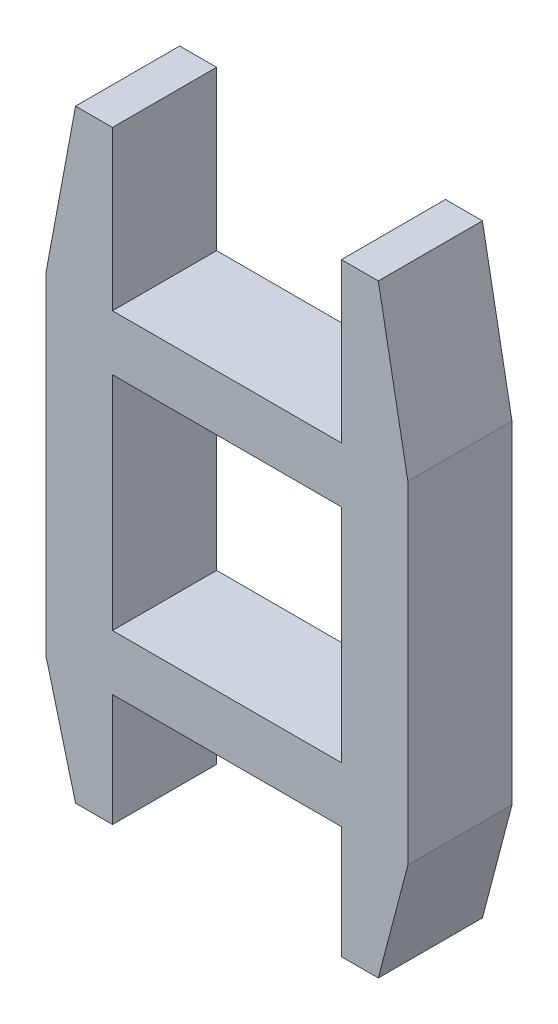
SolidWorks part; units mm, degrees
material "Acrylic (Medium-high impact)"
ref_plane "Front Plane" through (0, 0, 0) normal (0, 0, 1) x (1, 0, 0)
ref_plane "Top Plane" through (0, 0, 0) normal (0, 1, 0) x (1, 0, 0)
ref_plane "Right Plane" through (0, 0, 0) normal (1, 0, 0) x (0, 0, -1)
sketch "Sketch1" plane through (0, 0, 0) normal (0, 0, 1) x (1, 0, 0)
  line L0 (1247.2096, 961.8772) -> (1247.2096, 949.8772)
  line L1 (1263.2096, 948.3772) -> (1243.6096, 948.3772) construction
  line L2 (1247.2096, 946.8772) -> (1243.6096, 946.8772) construction
  line L3 (1247.2096, 961.8772) -> (1259.6096, 961.8772)
  line L4 (1245.2096, 973.4772) -> (1247.2096, 973.4772)
  line L5 (1247.2096, 973.4772) -> (1247.2096, 964.8772)
  line L6 (1247.2096, 955.8772) -> (1259.6096, 955.8772) construction
  line L7 (1259.6096, 964.8772) -> (1247.2096, 964.8772)
  line L8 (1243.6096, 964.8772) -> (1243.6096, 946.8772)
  line L9 (1243.6096, 946.8772) -> (1245.2096, 940.7772)
  line L10 (1247.2096, 964.8772) -> (1243.6096, 964.8772) construction
  line L11 (1259.6096, 946.8772) -> (1247.2096, 946.8772)
  line L12 (1243.6096, 964.8772) -> (1245.2096, 973.4772)
  line L13 (1247.2096, 940.7772) -> (1247.2096, 946.8772)
  line L14 (1245.2096, 940.7772) -> (1247.2096, 940.7772)
  line L15 (1247.2096, 949.8772) -> (1259.6096, 949.8772)
  line L16 (1259.6096, 964.8772) -> (1263.2096, 964.8772) construction
  line L17 (1259.6096, 946.8772) -> (1263.2096, 946.8772) construction
  line L18 (1261.6096, 940.7772) -> (1259.6096, 940.7772)
  line L19 (1253.4096, -37.9351) -> (1253.4096, 49962.0649) construction
  line L20 (1259.6096, 940.7772) -> (1259.6096, 946.8772)
  line L21 (1263.2096, 964.8772) -> (1261.6096, 973.4772)
  line L22 (1263.2096, 946.8772) -> (1261.6096, 940.7772)
  line L23 (1263.2096, 964.8772) -> (1263.2096, 946.8772)
  line L24 (1259.6096, 973.4772) -> (1259.6096, 964.8772)
  line L25 (1261.6096, 973.4772) -> (1259.6096, 973.4772)
  line L26 (1263.2096, 963.3772) -> (1243.6096, 963.3772) construction
  line L27 (1259.6096, 961.8772) -> (1259.6096, 949.8772)
  point P2 (1263.2096, 955.8772)
  point P14 (1243.6096, 955.8772)
  point P15 (1253.4096, 964.8772)
  point P20 (1253.4096, 963.3772)
  point P26 (1253.4096, 955.8772)
  point P28 (1253.4096, 964.8772)
  point P30 (1253.4096, 961.8772)
  point P31 (1253.4096, 948.3772)
  point P33 (1253.4096, 949.8772)
  point P36 (1253.4096, 946.8772)
  point P38 (1253.4096, 961.8772)
  dimension "D3" = 2
  dimension "D2" = 8.6
  dimension "D8" = 3.6
  dimension "D1" = 6.2
  dimension "D4" = 3
  dimension "D5" = 18
  dimension "D6" = 6.1
extrude "Boss-Extrude1" add sketch "Sketch1" along normal blind 5.64
equation "\"D5@Sketch1\" = \"boss_height@Servo<1>.Part\""
equation "\"D2@Sketch1\"=6.1+\"boss_thickness@Servo-1.Part\""
